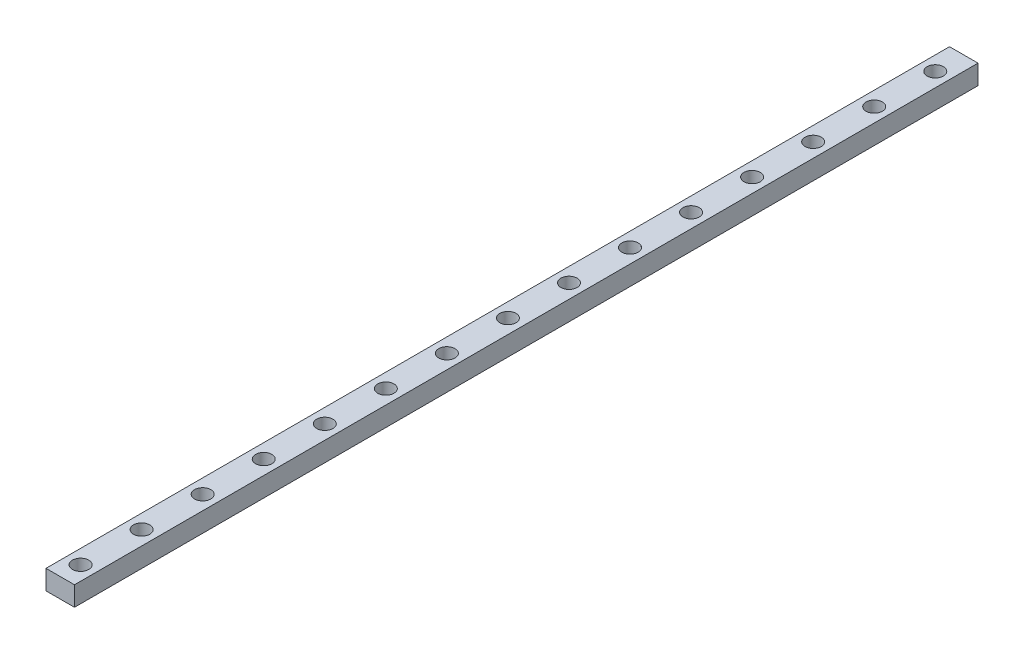
SolidWorks part; units mm, degrees
ref_plane "前视基准面" through (0, 0, 0) normal (0, 0, 1) x (1, 0, 0)
ref_plane "上视基准面" through (0, 0, 0) normal (0, 1, 0) x (1, 0, 0)
ref_plane "右视基准面" through (0, 0, 0) normal (1, 0, 0) x (0, 0, -1)
sketch "草图1" plane through (0, 0, 0) normal (0, 0, 1) x (1, 0, 0)
  line L1 (0, 0) -> (7, 0)
  line L2 (0, 0) -> (0, -4.8)
  line L3 (0, -4.8) -> (7, -4.8)
  line L4 (7, 0) -> (7, -4.8)
  dimension "D1" = 4.8
extrude "凸台-拉伸1" add sketch "草图1" along normal blind 280
sketch "草图2" plane through (0, 0, 0) normal (0, 1, 0) x (1, 0, 0)
  circle A0 centre (3.5, -5) radius 2
extrude "切除-拉伸1" cut sketch "草图2" against normal blind 3
pattern_linear "阵列(线性)1" count 19 spacing 15 along (0, 0, 1) of "切除-拉伸1"
sketch "草图3" plane through (0, -4.8, 0) normal (0, -1, 0) x (-1, 0, 0)
  circle A0 centre (-3.5, -5) radius 1
extrude "切除-拉伸2" cut sketch "草图3" against normal blind 3
pattern_linear "阵列(线性)2" count 19 spacing 15 along (0, 0, 1) of "切除-拉伸2"
sketch "草图4" plane through (0, 0, 0) normal (0, 1, 0) x (1, 0, 0)
  line L0 (0, -280) -> (0, 0) construction
  line L1 (0, -58) -> (7, -58)
  line L2 (0, -58) -> (0, 0)
  line L3 (0, 0) -> (7, 0)
  line L4 (7, -58) -> (7, 0)
  circle A0 centre (3.5, -65) radius 2 construction
  dimension "D1" = 7
extrude "切除-拉伸3" cut sketch "草图4" against normal blind 10
